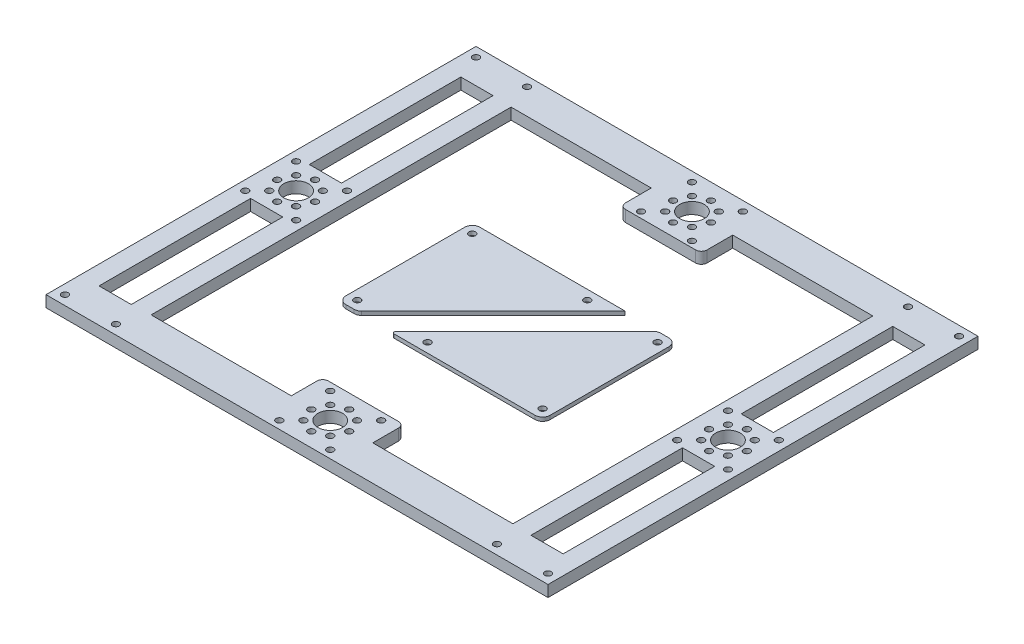
SolidWorks part; units mm, degrees
ref_plane "Plan de face" through (0, 0, 0) normal (0, 0, 1) x (1, 0, 0)
ref_plane "Plan de dessus" through (0, 0, 0) normal (0, 1, 0) x (1, 0, 0)
ref_plane "Plan de droite" through (0, 0, 0) normal (1, 0, 0) x (0, 0, -1)
sketch "Esquisse1" plane through (0, 0, 0) normal (0, 1, 0) x (1, 0, 0)
  line L0 (0, 0) -> (265, 0)
  line L1 (0, 0) -> (0, -227)
  line L2 (0, -227) -> (265, -227)
  line L3 (265, -227) -> (265, 0)
  line L7 (37, -35.0701) -> (228, -35.0701)
  line L8 (228, -35.0701) -> (228, -191.9299)
  line L9 (228, -191.9299) -> (37, -191.9299)
  line L10 (37, -191.9299) -> (37, -35.0701)
  line L19 (238, -98) -> (255, -98)
  line L22 (238, -18) -> (238, -98)
  line L23 (238, -18) -> (255, -18)
  line L24 (255, -18) -> (255, -98)
  line L29 (238, -209) -> (238, -129)
  line L30 (238, -209) -> (255, -209)
  line L31 (255, -209) -> (255, -129)
  line L32 (238, -129) -> (255, -129)
  line L33 (27, -18) -> (27, -98)
  line L34 (27, -18) -> (10, -18)
  line L35 (10, -18) -> (10, -98)
  line L36 (27, -98) -> (10, -98)
  line L37 (27, -209) -> (10, -209)
  line L38 (10, -209) -> (10, -129)
  line L39 (27, -129) -> (10, -129)
  line L40 (27, -209) -> (27, -129)
  circle A0 centre (246.5, -113.5) radius 6.5
  circle A1 centre (246.5, -103.5) radius 1.75
  circle A2 centre (253.5711, -106.4289) radius 1.75
  circle A3 centre (256.5, -113.5) radius 1.75
  circle A4 centre (253.5711, -120.5711) radius 1.75
  circle A5 centre (246.5, -123.5) radius 1.75
  circle A6 centre (239.4289, -120.5711) radius 1.75
  circle A7 centre (236.5, -113.5) radius 1.75
  circle A8 centre (239.4289, -106.4289) radius 1.75
  circle A9 centre (259.935, -100.065) radius 1.75
  circle A10 centre (259.935, -126.935) radius 1.75
  circle A11 centre (233.065, -100.065) radius 1.75
  circle A12 centre (233.065, -126.935) radius 1.75
  circle A13 centre (132.5, -209.465) radius 6.5
  circle A14 centre (132.5, -199.465) radius 1.75
  circle A15 centre (139.5711, -202.3939) radius 1.75
  circle A16 centre (142.5, -209.465) radius 1.75
  circle A17 centre (139.5711, -216.536) radius 1.75
  circle A18 centre (132.5, -219.465) radius 1.75
  circle A19 centre (125.4289, -216.536) radius 1.75
  circle A20 centre (122.5, -209.465) radius 1.75
  circle A21 centre (125.4289, -202.3939) radius 1.75
  circle A22 centre (145.935, -196.0299) radius 1.75
  circle A23 centre (145.935, -222.9) radius 1.75
  circle A24 centre (119.065, -196.0299) radius 1.75
  circle A25 centre (119.065, -222.9) radius 1.75
  circle A26 centre (18.514, -113.5) radius 6.5
  circle A27 centre (18.514, -103.5) radius 1.75
  circle A28 centre (25.585, -106.4289) radius 1.75
  circle A29 centre (28.514, -113.5) radius 1.75
  circle A30 centre (25.585, -120.5711) radius 1.75
  circle A31 centre (18.514, -123.5) radius 1.75
  circle A32 centre (11.4429, -120.5711) radius 1.75
  circle A33 centre (8.514, -113.5) radius 1.75
  circle A34 centre (11.4429, -106.4289) radius 1.75
  circle A35 centre (31.949, -100.065) radius 1.75
  circle A36 centre (31.949, -126.935) radius 1.75
  circle A37 centre (5.0789, -100.065) radius 1.75
  circle A38 centre (5.0789, -126.935) radius 1.75
  circle A39 centre (132.5, -18.5) radius 6.5
  circle A40 centre (132.5, -8.5) radius 1.75
  circle A41 centre (139.5711, -11.4289) radius 1.75
  circle A42 centre (142.5, -18.5) radius 1.75
  circle A43 centre (139.5711, -25.5711) radius 1.75
  circle A44 centre (132.5, -28.5) radius 1.75
  circle A45 centre (125.4289, -25.5711) radius 1.75
  circle A46 centre (122.5, -18.5) radius 1.75
  circle A47 centre (125.4289, -11.4289) radius 1.75
  circle A48 centre (145.935, -5.065) radius 1.75
  circle A49 centre (145.935, -31.935) radius 1.75
  circle A50 centre (119.065, -5.065) radius 1.75
  circle A51 centre (119.065, -31.935) radius 1.75
  circle A52 centre (260, -5) radius 1.75
  circle A53 centre (233.065, -5) radius 1.75
  circle A60 centre (260, -222) radius 1.75
  circle A61 centre (233.065, -222) radius 1.75
  circle A62 centre (5, -5) radius 1.75
  circle A63 centre (31.935, -5) radius 1.75
  circle A64 centre (5, -222) radius 1.75
  circle A65 centre (31.935, -222) radius 1.75
  dimension "D1" = 265
  dimension "D2" = 227
  dimension "D3" = 227
extrude "Boss.-Extru.1" add sketch "Esquisse1" along normal blind 6
sketch "Esquisse2" plane through (0, 6, 0) normal (0, 1, 0) x (1, 0, 0)
  line L2 (37, -18.5) -> (37, -35.0701)
  line L3 (37, -18.5) -> (110.9884, -18.5)
  line L4 (110.9884, -18.5) -> (110.9884, -35.0701)
  line L5 (228, -35.0701) -> (37, -35.0701) construction
  line L6 (110.9884, -35.0701) -> (37, -35.0701)
  line L9 (154.0116, -35.0701) -> (228, -35.0701)
  line L10 (154.0116, -18.5) -> (154.0116, -35.0701)
  line L11 (228, -18.5) -> (154.0116, -18.5)
  line L12 (228, -18.5) -> (228, -35.0701)
  line L13 (228, -208.5) -> (228, -191.9299)
  line L14 (228, -208.5) -> (154.0116, -208.5)
  line L15 (154.0116, -208.5) -> (154.0116, -191.9299)
  line L16 (154.0116, -191.9299) -> (228, -191.9299)
  line L17 (110.9884, -191.9299) -> (37, -191.9299)
  line L18 (110.9884, -208.5) -> (110.9884, -191.9299)
  line L19 (37, -208.5) -> (110.9884, -208.5)
  line L20 (37, -208.5) -> (37, -191.9299)
extrude "Enlèv. mat.-Extru.1" cut sketch "Esquisse2" against normal blind 10
fillet "Congé1" radius 3 4 edges at (154.0116, 3, 191.9299) (110.9884, 3, 191.9299) (154.0116, 3, 35.0701) (110.9884, 3, 35.0701)
sketch "Esquisse3" plane through (0, 0, 0) normal (0, -1, 0) x (1, 0, 0)
  line L0 (75.6788, 148.3661) -> (85.6788, 148.3661)
  line L1 (85.6788, 148.3661) -> (156.3895, 77.6555)
  line L2 (156.3895, 77.6555) -> (75.6788, 77.6555)
  line L3 (75.6788, 77.6555) -> (75.6788, 148.3661)
  line L4 (184.1959, 78.3392) -> (174.1959, 78.3392)
  line L5 (174.1959, 78.3392) -> (103.4853, 149.0499)
  line L6 (103.4853, 149.0499) -> (184.1959, 149.0499)
  line L7 (184.1959, 149.0499) -> (184.1959, 78.3392)
  line L8 (0, 227) -> (265, 227)
  line L9 (265, 227) -> (265, 0)
  circle A0 centre (80.6788, 143.3661) radius 1.75
  circle A1 centre (141.3895, 82.6555) radius 1.75
  circle A2 centre (80.6788, 82.6555) radius 1.75
  circle A3 centre (179.1959, 83.3392) radius 1.75
  circle A4 centre (118.4853, 144.0499) radius 1.75
  circle A5 centre (179.1959, 144.0499) radius 1.75
extrude "Boss.-Extru.2" add sketch "Esquisse3" against normal blind 2 separate body contours L3 L2 L1 L0 A2 A1 A0 | L7 L6 L5 L4 A5 A4 A3
fillet "Congé2" radius 4 3 edges at (85.6788, 1, 148.3661) (75.6788, 1, 148.3661) (75.6788, 1, 77.6555)
fillet "Congé3" radius 4 3 edges at (174.1959, 1, 78.3392) (184.1959, 1, 78.3392) (184.1959, 1, 149.0499)
fillet "Congé4" radius 1 1 edges at (103.4853, 1, 149.0499)
